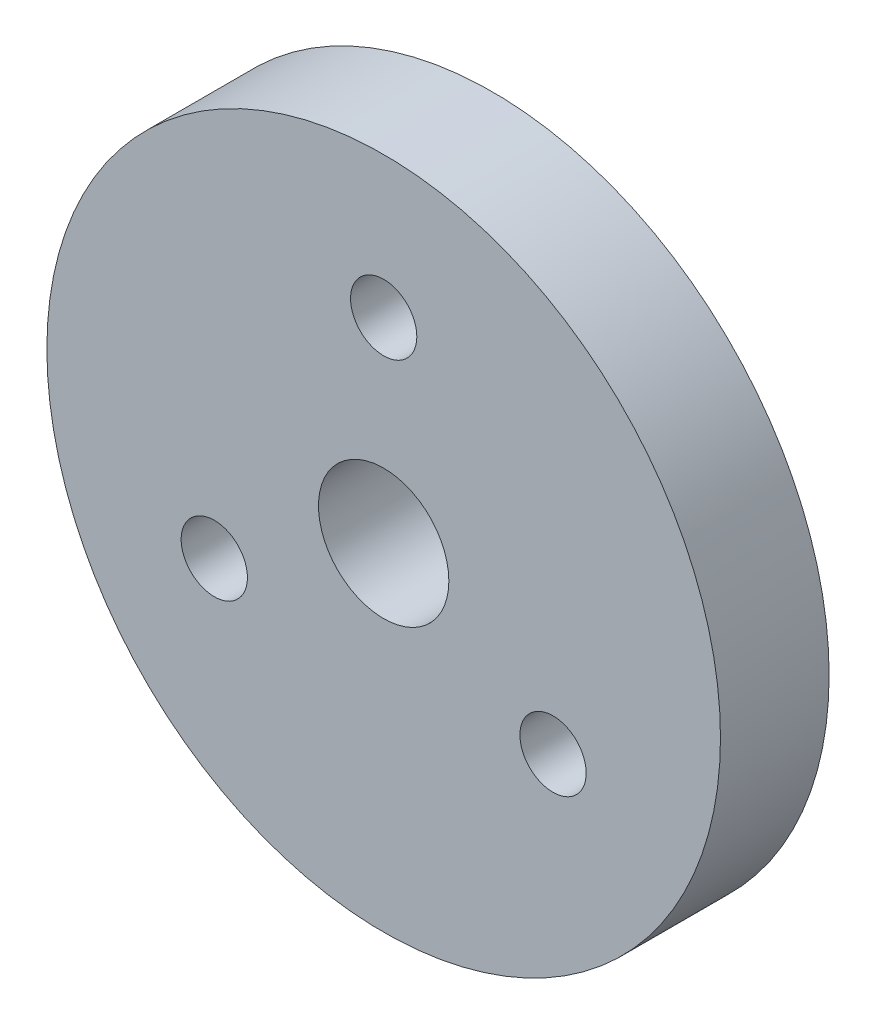
SolidWorks part; units mm, degrees
ref_plane "Front Plane" through (0, 0, 0) normal (0, 0, 1) x (1, 0, 0)
ref_plane "Top Plane" through (0, 0, 0) normal (0, 1, 0) x (1, 0, 0)
ref_plane "Right Plane" through (0, 0, 0) normal (1, 0, 0) x (0, 0, -1)
sketch "Sketch1" plane through (0, 0, 0) normal (0, 0, 1) x (1, 0, 0)
  circle A0 centre (0, 0) radius 15.5
  dimension "D1" = 31
extrude "Boss-Extrude1" add sketch "Sketch1" along normal blind 5
sketch "Sketch2" plane through (0, 0, 5) normal (0, 0, 1) x (1, 0, 0)
  circle A0 centre (0, 0) radius 3
  dimension "D1" = 6
extrude "Cut-Extrude1" cut sketch "Sketch2" against normal up to next
sketch "Sketch3" plane through (0, 0, 5) normal (0, 0, 1) x (1, 0, 0)
  circle A1 centre (0, 9) radius 1.525
  circle A2 centre (7.7942, -4.5) radius 1.525
  circle A3 centre (-7.7942, -4.5) radius 1.525
  point P12 (0, 0)
  dimension "D2" = 3.05
  dimension "D3" = 3
extrude "Cut-Extrude2" cut sketch "Sketch3" against normal through all both and the other way through all
